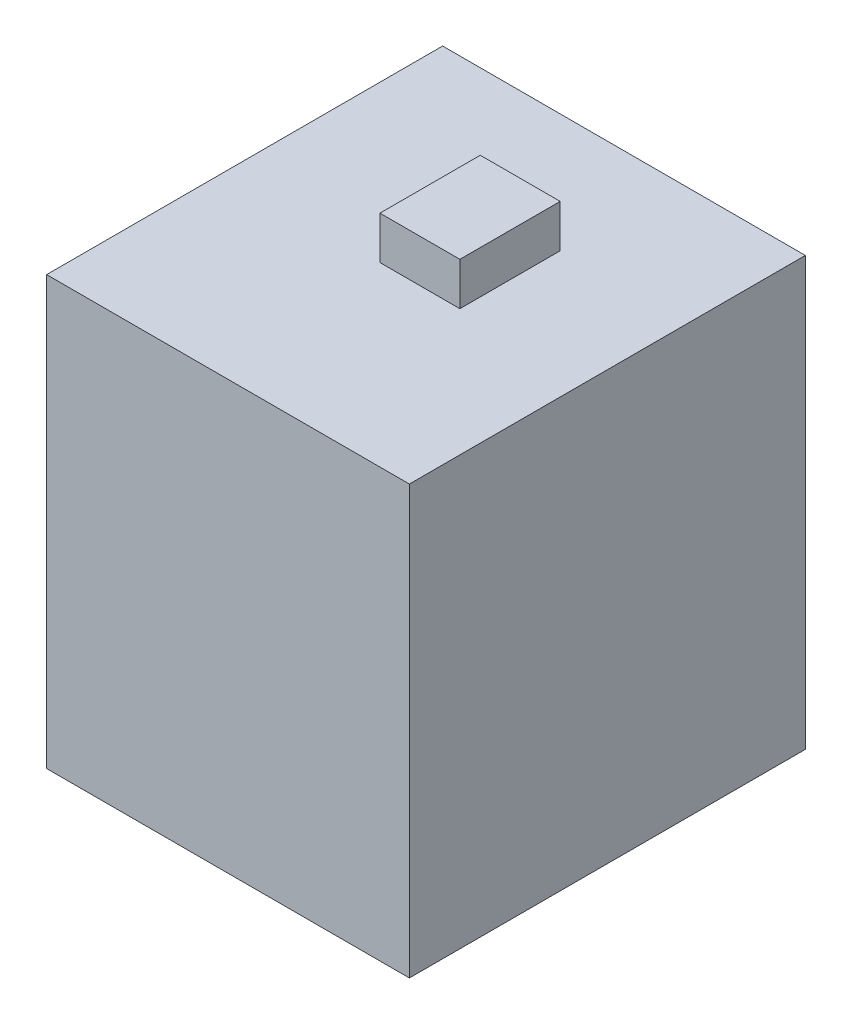
SolidWorks part; units mm, degrees
ref_plane "Front Plane" through (0, 0, 0) normal (0, 0, 1) x (1, 0, 0)
ref_plane "Top Plane" through (0, 0, 0) normal (0, 1, 0) x (1, 0, 0)
ref_plane "Right Plane" through (0, 0, 0) normal (1, 0, 0) x (0, 0, -1)
sketch "Sketch1" plane through (0, 0, 0) normal (0, 1, 0) x (1, 0, 0)
  line L1 (-36.5147, 51.1649) -> (48.2793, 51.1649)
  line L2 (-36.5147, 51.1649) -> (-36.5147, -41.3981)
  line L3 (-36.5147, -41.3981) -> (48.2793, -41.3981)
  line L4 (48.2793, 51.1649) -> (48.2793, -41.3981)
extrude "Boss-Extrude1" add sketch "Sketch1" along normal blind 100
sketch "Sketch2" plane through (0, 100, 0) normal (0, 1, 0) x (1, 0, 0)
  line L1 (0, 0) -> (18.6827, 0)
  line L2 (0, 0) -> (0, 23.4498)
  line L3 (0, 23.4498) -> (18.6827, 23.4498)
  line L4 (18.6827, 0) -> (18.6827, 23.4498)
extrude "Boss-Extrude2" add sketch "Sketch2" along normal blind 10
